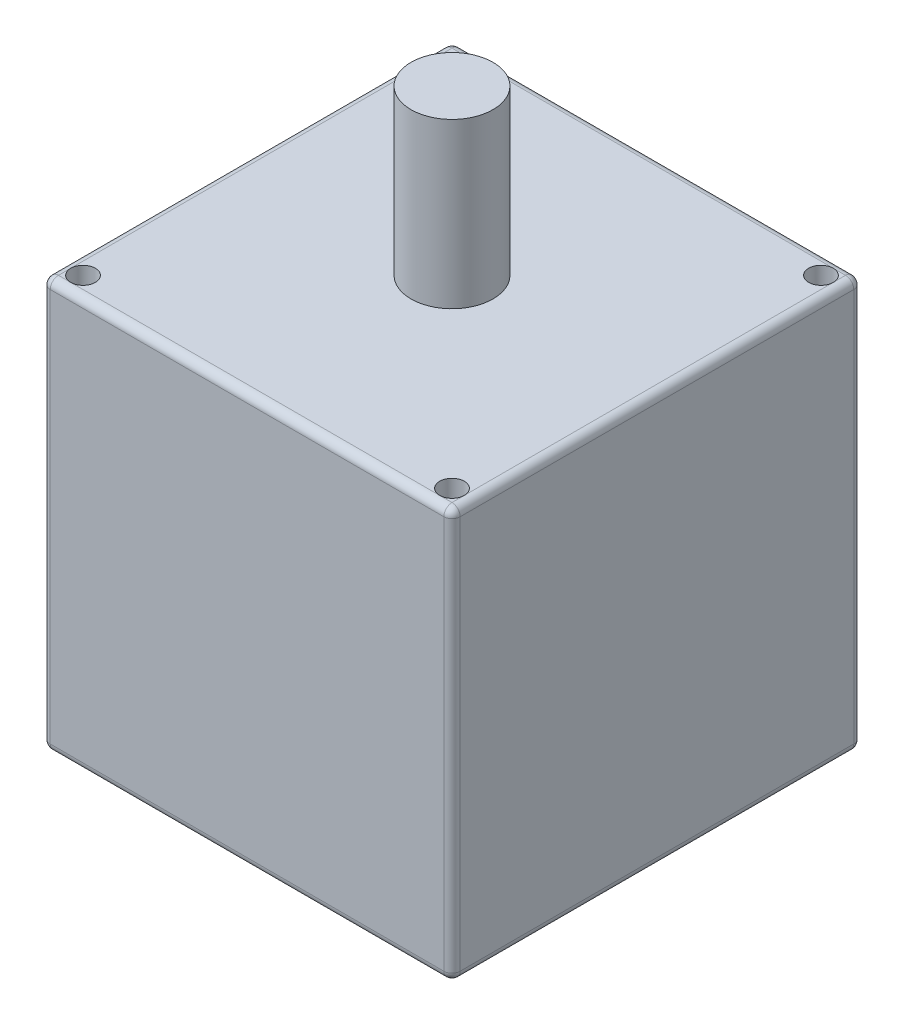
SolidWorks part; units mm, degrees
ref_plane "Front Plane" through (0, 0, 0) normal (0, 0, 1) x (1, 0, 0)
ref_plane "Top Plane" through (0, 0, 0) normal (0, 1, 0) x (1, 0, 0)
ref_plane "Right Plane" through (0, 0, 0) normal (1, 0, 0) x (0, 0, -1)
sketch "Sketch1" plane through (0, 0, 0) normal (0, 1, 0) x (1, 0, 0)
  line L1 (-25, 25) -> (25, 25)
  line L2 (-25, 25) -> (-25, -25)
  line L3 (-25, -25) -> (25, -25)
  line L4 (25, 25) -> (25, -25)
  line L5 (-25, 25) -> (25, -25) construction
  line L6 (-25, -25) -> (25, 25) construction
  point P0 (0, 0)
  dimension "D1" = 50
  dimension "D2" = 50
extrude "Boss-Extrude1" add sketch "Sketch1" along normal blind 50
fillet "Fillet1" radius 1 12 edges at (-25, 0, 0) (-25, 25, -25) (0, 0, -25) (25, 25, -25) (25, 0, 0) (-25, 25, 25) (25, 25, 25) (0, 0, 25) (0, 50, 25) (-25, 50, 0) (0, 50, -25) (25, 50, 0)
sketch "Sketch2" plane through (0, 50, 0) normal (0, 1, 0) x (1, 0, 0)
  line L1 (-22.5, -22.5) -> (22.5, -22.5)
  line L2 (-22.5, -22.5) -> (-22.5, 22.5)
  line L3 (-22.5, 22.5) -> (22.5, 22.5)
  line L4 (22.5, -22.5) -> (22.5, 22.5)
  line L5 (-22.5, -22.5) -> (22.5, 22.5) construction
  line L6 (-22.5, 22.5) -> (22.5, -22.5) construction
  point P0 (0, 0)
  dimension "D1" = 45
  dimension "D2" = 45
hole_wizard "Ø3.0mm Dowel Hole1" positions "Sketch3" profile "Sketch4" hole size "Ø3.0" standard "ANSI Metric"
sketch "Sketch3" plane through (0, 50, 0) normal (0, 1, 0) x (1, 0, 0)
  point P0 (-22.5, 22.5)
  point P3 (22.5, 22.5)
  point P6 (22.5, -22.5)
  point P9 (-22.5, -22.5)
sketch "Sketch4" plane through (-22.5, 50, -22.5) normal (1, 0, 0) x (0, 0, 1)
  line L0 (0, 0) -> (0, 10.9013)
  line L1 (0, 10.9013) -> (1.5, 10)
  line L2 (1.5, 10) -> (1.5, 0)
  line L5 (1.5, 0) -> (0, 0)
  line L10 (0, 10.9013) -> (-1.5, 10) construction
  line L11 (0, -6.35) -> (0, 107.95) construction
  dimension "Hole Dia." = 3
  dimension "Hole Depth" = 10
  dimension "Drill Angle" = 118
sketch "Sketch5" plane through (0, 50, 0) normal (0, 1, 0) x (1, 0, 0)
  circle A0 centre (0, 0) radius 5
  dimension "D1" = 10
extrude "Boss-Extrude2" add sketch "Sketch5" along normal blind 20
